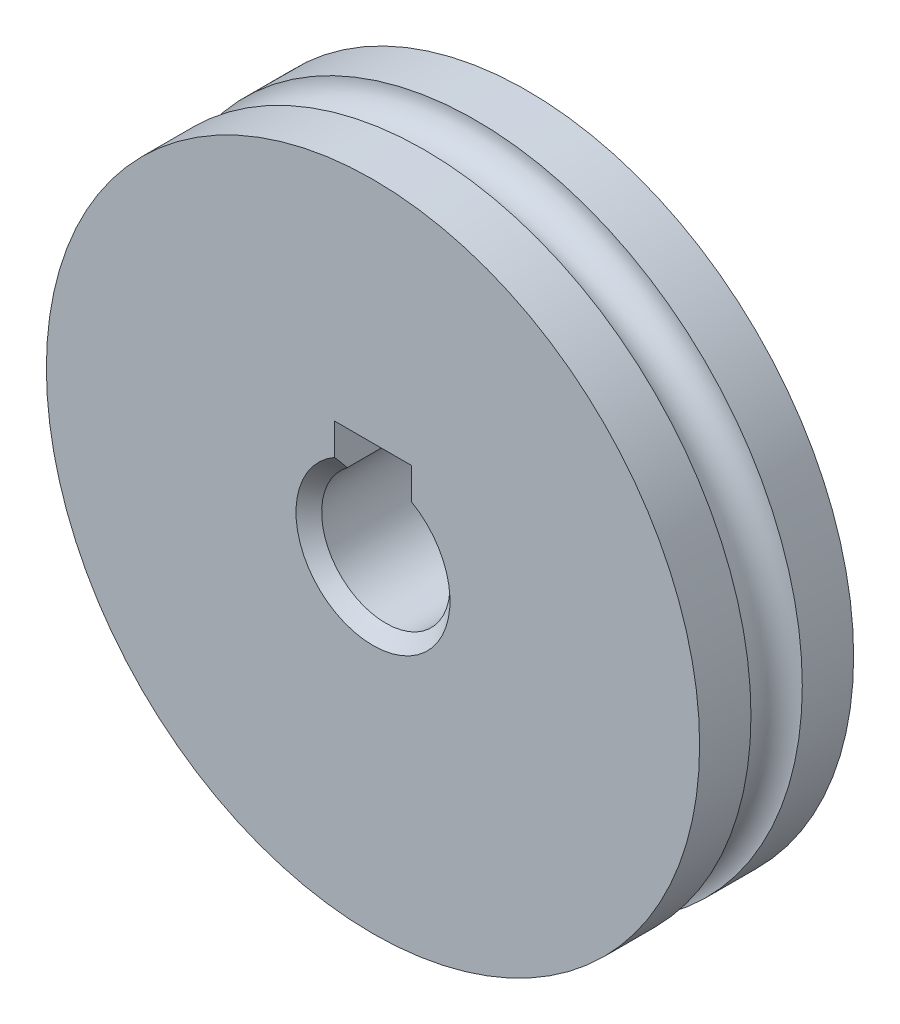
SolidWorks part; units mm, degrees
ref_plane "前视基准面" through (0, 0, 0) normal (0, 0, 1) x (1, 0, 0)
ref_plane "上视基准面" through (0, 0, 0) normal (0, 1, 0) x (1, 0, 0)
ref_plane "右视基准面" through (0, 0, 0) normal (1, 0, 0) x (0, 0, -1)
sketch "草图3" plane through (0, 0, 0) normal (0, 0, 1) x (1, 0, 0)
  circle A0 centre (0, 0) radius 25.45
  circle A1 centre (0, 0) radius 5
  dimension "D1" = 50.9
  dimension "D2" = 10
extrude "凸台-拉伸1" add sketch "草图3" along normal blind 12
sketch "草图6" plane through (0, 0, 0) normal (0, 1, 0) x (1, 0, 0)
  line L0 (25.45, -12) -> (25.45, 0) construction
  circle A0 centre (25.45, -6) radius 2
  point P0 (25.45, -6)
  dimension "D1" = 4
sketch "草图7" plane through (0, 0, 0) normal (0, 1, 0) x (1, 0, 0)
  line L0 (0, 0) -> (0, 15.4077)
chamfer "倒角1" distance 1 angle 45 2 edges at (5, 0, 0) (5, 0, 12)
sketch "草图8" plane through (0, 0, 0) normal (0, 0, -1) x (-1, 0, 0)
  line L0 (0, 7.65) -> (-3, 7.65)
  line L1 (0, 0) -> (3, 0)
  line L3 (0, 7.65) -> (3, 7.65)
  line L4 (3, 0) -> (3, 7.65)
  line L5 (-3, 7.65) -> (-3, 0)
  line L6 (-3, 0) -> (0, 0)
  line L7 (-3, 7.65) -> (0, 7.65)
  circle M1 centre (0, 0) radius 6
  dimension "D1" = 7.65
  dimension "D2" = 3
  dimension "D3" = 3
extrude "切除-拉伸1" cut sketch "草图8" against normal blind 19 contours L5 L6 L1 L4 M1 | L0 L5 L4 L3 M1
revolve "切除-旋转1" cut sketch "草图6" angle 360 about L0
ref_plane "基准面1" through (0, 0, 6) normal (0, 0, 1) x (1, 0, 0)
